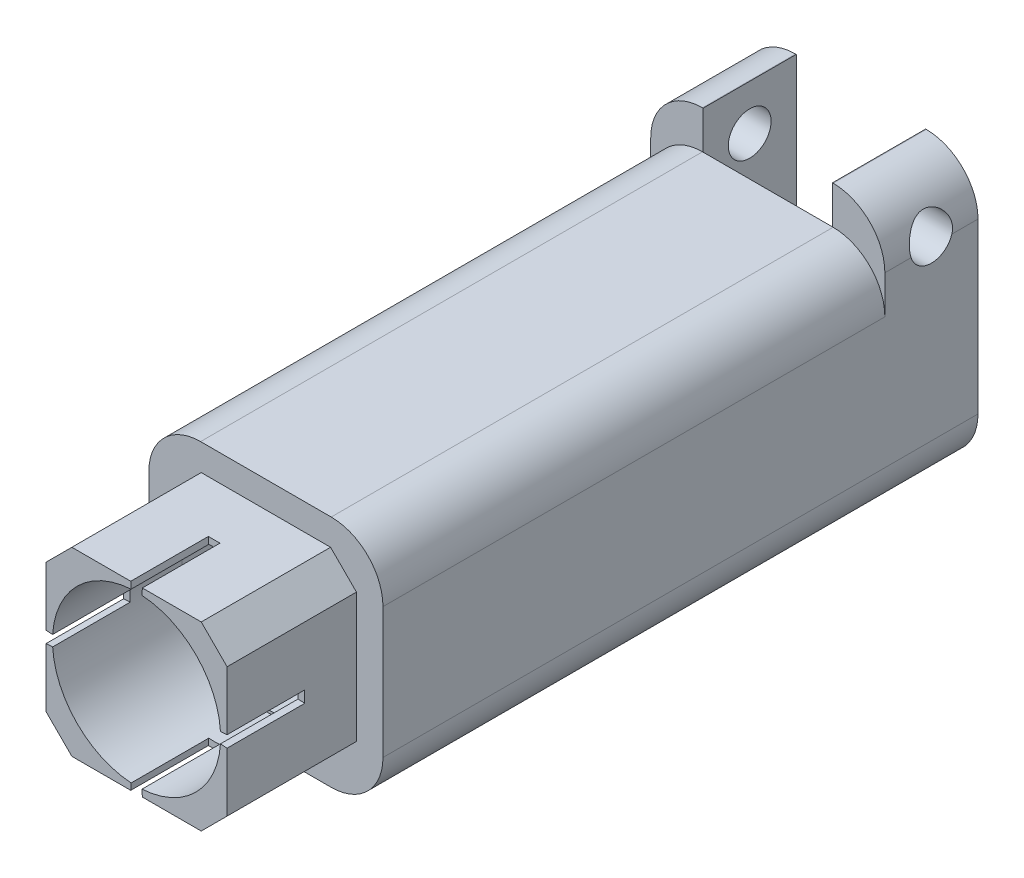
SolidWorks part; units mm, degrees
ref_plane "Front Plane" through (0, 0, 0) normal (0, 0, 1) x (1, 0, 0)
ref_plane "Top Plane" through (0, 0, 0) normal (0, 1, 0) x (1, 0, 0)
ref_plane "Right Plane" through (0, 0, 0) normal (1, 0, 0) x (0, 0, -1)
sketch "Sketch1" plane through (0, 0, 0) normal (0, 0, 1) x (1, 0, 0)
  line L0 (-5.05, 9.05) -> (5.05, 9.05)
  line L1 (9.05, -5.05) -> (9.05, 5.05)
  line L2 (0, 0) -> (0, 14.1446) construction
  line L3 (-9.05, -5.05) -> (-9.05, 5.05)
  line L4 (-12.732, 0) -> (15.0845, 0) construction
  line L5 (-5.05, -9.05) -> (5.05, -9.05)
  arc A4 (5.05, 9.05) -> (9.05, 5.05) centre (5.05, 5.05) cw
  arc A5 (9.05, -5.05) -> (5.05, -9.05) centre (5.05, -5.05) cw
  arc A6 (-5.05, -9.05) -> (-9.05, -5.05) centre (-5.05, -5.05) cw
  arc A7 (-9.05, 5.05) -> (-5.05, 9.05) centre (-5.05, 5.05) cw
  point P11 (9.05, 0)
  point P12 (0, 9.05)
  point P20 (0, -9.05)
  point P21 (-9.05, 0)
  dimension "D3" = 0
  dimension "D1" = 5.05
  dimension "D2" = 5.05
  dimension "D4" = 9.05
  dimension "D5" = 9.05
extrude "Boss-Extrude1" add sketch "Sketch1" along normal blind 46
sketch "Sketch3" plane through (0, 0, 46) normal (0, 0, 1) x (1, 0, 0)
  line L0 (-5, -7) -> (5, -7)
  line L1 (-7, -5) -> (-7, 5)
  line L2 (-5, 7) -> (5, 7)
  line L3 (7, -5) -> (7, 5)
  line L4 (-7, -7) -> (7, 7) construction
  line L5 (-7, 7) -> (7, -7) construction
  line L6 (5, 7) -> (7, 5)
  line L7 (-5, 7) -> (-7, 5)
  line L8 (-7, -5) -> (-5, -7)
  line L9 (5, -7) -> (7, -5)
  circle A6 centre (0, 0) radius 6.5
  point P3 (0, 0)
  dimension "D1" = 14
  dimension "D3" = 13
  dimension "D4" = 0
  dimension "D5" = 0
  dimension "D6" = 0
extrude "Boss-Extrude2" add sketch "Sketch3" along normal blind 10
sketch "Sketch11" plane through (0, 0, 56) normal (0, 0, 1) x (1, 0, 0)
  line L0 (0, 0) -> (7, 0.45)
  line L1 (7, -5) -> (7, 5) construction
  line L2 (7, 0.45) -> (7, -0.45)
  line L3 (7, -0.45) -> (0, 0)
  dimension "D1" = 0.45
  dimension "D2" = 0.45
extrude "Cut-Extrude7" cut sketch "Sketch11" against normal blind 6
pattern_circular "CirPattern1" count 4 over 360 about axis through (0, 0, 56) along (0, 0, -1) of "Cut-Extrude7"
sketch "Sketch12" plane through (0, 0, 46) normal (0, 0, 1) x (1, 0, 0)
  line L0 (0, 0) -> (0, 14.1446) construction
  circle A0 centre (0, 0.1925) radius 6.5
  dimension "D1" = 13
extrude "Cut-Extrude8" cut sketch "Sketch12" against normal blind 30
sketch "Sketch15" plane through (0, 0, 0) normal (0, 0, 1) x (1, 0, 0)
  line L0 (9.05, -5.05) -> (9.05, 5.05) construction
  line L6 (-5.05, -9.05) -> (5.05, -9.05)
  line L7 (-9.05, -5.05) -> (-9.05, 8)
  line L8 (-5.05, 12) -> (5.05, 12)
  line L9 (9.05, -5.05) -> (9.05, 8)
  line L10 (-5.05, -9.05) -> (5.05, -9.05) construction
  line L11 (-9.05, -5.05) -> (-9.05, 5.05) construction
  arc A4 (-5.05, -9.05) -> (-9.05, -5.05) centre (-5.05, -5.05) cw
  arc A5 (5.05, -9.05) -> (9.05, -5.05) centre (5.05, -5.05) ccw
  arc A6 (5.05, 12) -> (9.05, 8) centre (5.05, 8) cw
  arc A7 (-9.05, 8) -> (-5.05, 12) centre (-5.05, 8) cw
  point P0 (0, 0)
  dimension "D2" = 0
  dimension "D5" = 4
  dimension "D1" = 12
  dimension "D3" = 0
  dimension "D4" = 0
extrude "Boss-Extrude3" add sketch "Sketch15" along normal blind 7.2
sketch "Sketch17" plane through (9.05, 0, 0) normal (1, 0, 0) x (0, 0, -1)
  line L0 (-7.2, 12) -> (0, 12) construction
  line L1 (-7.2, 5.05) -> (-7.2, 8) construction
  circle A0 centre (-3.6, 8.5) radius 1.655
  dimension "D1" = 3.31
  dimension "D2" = 3.5
  dimension "D3" = 3.6
extrude "Cut-Extrude10" cut sketch "Sketch17" against normal blind 30
sketch "Sketch18" plane through (0, 0, 0) normal (0, 0, 1) x (1, 0, 0)
  circle A0 centre (0, 0) radius 5
  dimension "D1" = 10
extrude "Cut-Extrude11" cut sketch "Sketch18" along normal blind 6
sketch "Sketch19" plane through (0, 0, 0) normal (0, 0, 1) x (1, 0, 0)
  line L5 (-0.5, 4.9749) -> (0, 4.4555)
  line L6 (0, 0) -> (0, 14.1446) construction
  line L7 (0, 4.4555) -> (0.5, 4.9749)
  circle A0 centre (0, 0) radius 5 construction
  arc A1 (-0.5, 4.9749) -> (0.5, 4.9749) centre (0, 4.9749) cw
  dimension "D1" = 0.5
  dimension "D2" = 0.5
extrude "Boss-Extrude4" add sketch "Sketch19" along normal blind 6
pattern_circular "CirPattern2" count 36 every 10 about axis through (0, 0, 0) along (0, 0, 1) of "Boss-Extrude4"
sketch "Sketch20" plane through (0, 0, 6) normal (0, 0, -1) x (-1, 0, 0)
  circle A0 centre (0, 0) radius 6.5
  dimension "D1" = 13
extrude "Cut-Extrude12" cut sketch "Sketch20" against normal blind 1.2
sketch "Sketch21" plane through (0, 0, 0) normal (0, 0, 1) x (1, 0, 0)
  line L0 (-12.732, 0) -> (15.0845, 0) construction
  line L1 (5, 0) -> (-5, 0)
  line L2 (5, 0) -> (5, 17.4937)
  line L3 (5, 17.4937) -> (-5, 17.4937)
  line L4 (-5, 0) -> (-5, 17.4937)
  dimension "D1" = 5
  dimension "D2" = 5
extrude "Cut-Extrude13" cut sketch "Sketch21" along normal blind 7.2
